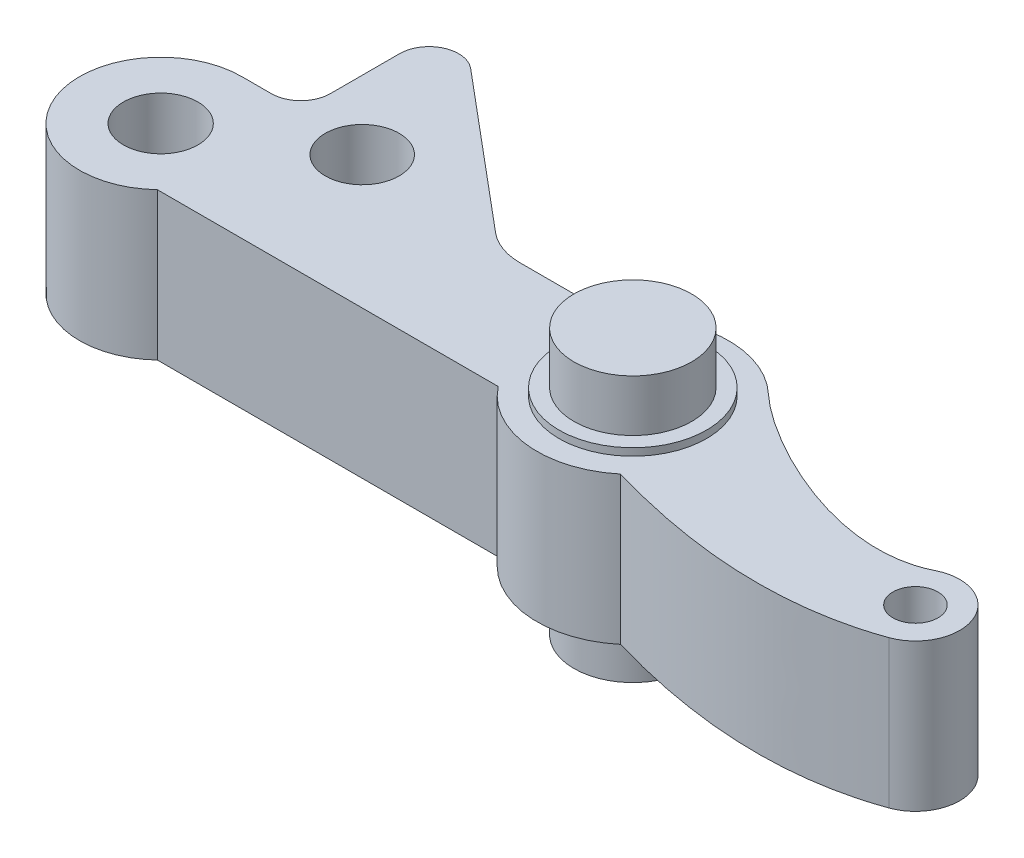
SolidWorks part; units mm, degrees
ref_plane "前视基准面" through (0, 0, 0) normal (0, 0, 1) x (1, 0, 0)
ref_plane "上视基准面" through (0, 0, 0) normal (0, 1, 0) x (1, 0, 0)
ref_plane "右视基准面" through (0, 0, 0) normal (1, 0, 0) x (0, 0, -1)
other "Configuration Table"
sketch "草图1" plane through (0, 0, 0) normal (0, 1, 0) x (1, 0, 0)
  line L0 (-5.1235, -4) -> (-28.2251, -4)
  line L1 (0, 0) -> (-38.4813, 0) construction
  line L2 (-5.1235, 4) -> (-13.1235, 4)
  line L3 (-23.3397, 5) -> (-32, 0) construction
  line L4 (-13.1235, 4) -> (-28, 16.4829)
  line L5 (-28, 16.4829) -> (-28, 5.5)
  line L6 (-32, 5.5) -> (-28, 5.5)
  arc A0 (-5.1235, -4) -> (-5.1235, 4) centre (0, 0) ccw
  arc A1 (-32, 5.5) -> (-28.2251, -4) centre (-32, 0) ccw
  circle A2 centre (-32, 0) radius 2.525
  circle A3 centre (-23.3397, 5) radius 2.505
  dimension "D1" = 13
  dimension "D2" = 11
  dimension "D5" = 5.05
  dimension "D8" = 5.01
  dimension "D3" = 32
  dimension "D4" = 4
  dimension "D6" = 30
  dimension "D7" = 10
  dimension "D9" = 4
  dimension "D10" = 8
  dimension "D11" = 40
extrude "凸台-拉伸1" add sketch "草图1" along normal blind 10
ref_plane "基准面3" through (0, 5, 0) normal (0, -1, 0) x (-1, 0, 0)
sketch "草图2" plane through (0, 5, 0) normal (0, 1, 0) x (1, 0, 0)
  line L0 (0, 0) -> (30.1993, 0) construction
  line L1 (0, 0) -> (21.836, -2.6811) construction
  line L7 (4.1594, -4.9949) -> (15.251, -8.2326) construction
  line L8 (15.251, -8.2326) -> (22.8497, -5.5047) construction
  line L9 (4.4667, 4.7222) -> (7.2849, 2.0565) construction
  line L10 (15.7167, -2.3962) -> (20.4901, 0) construction
  line L11 (7.2849, 2.0565) -> (15.7167, -2.3962) construction
  arc A0 (-5.1235, -4) -> (-5.1235, 4) centre (0, 0) ccw construction
  circle A2 centre (21.836, -2.6811) radius 1.525
  arc A3 (22.8497, -5.5047) -> (20.4901, 0) centre (21.836, -2.6811) ccw
  arc A4 (4.1594, -4.9949) -> (4.4667, 4.7222) centre (0, 0) ccw
  spline S0 degree 2 poles (4.1594, -4.9949) (15.251, -8.2326) (22.8497, -5.5047) knots 0 0 0 1 1 1
  spline S1 degree 3 poles (4.4667, 4.7222) (7.2849, 2.0565) (15.7167, -2.3962) (20.4901, 0) knots 0 0 0 0 1 1 1 1
  dimension "D4" = 3.05
  dimension "D3" = 6
  dimension "D1" = 7
  dimension "D2" = 22
extrude "凸台-拉伸2" add sketch "草图2" along normal mid plane 10 contours A4 S1 A3 S0 A2
sketch "草图3" plane through (0, 10, 0) normal (0, 1, 0) x (1, 0, 0)
  circle A0 centre (0, 0) radius 22
ref_plane "基准面1" through (0, 5, 0) normal (0, 1, 0) x (1, 0, 0)
sketch "草图5" plane through (0, 5, 0) normal (0, 1, 0) x (1, 0, 0)
  circle A0 centre (0, 0) radius 3.99
  dimension "D1" = 7.98
extrude "凸台-拉伸4" add sketch "草图5" along normal mid plane 18
fillet "圆角1" radius 4 1 edges at (-13.1235, 5, -4)
fillet "圆角2" radius 2 1 edges at (-28, 5, -16.4829)
fillet "圆角3" radius 2 1 edges at (-28, 5, -5.5)
sketch "草图6" plane through (0, 10, 0) normal (0, 1, 0) x (1, 0, 0)
  circle A0 centre (0, 0) radius 5
  dimension "D1" = 10
extrude "凸台-拉伸5" add sketch "草图6" along normal blind 0.5
ref_plane "基准面4" through (0, 5, 0) normal (0, 1, 0) x (1, 0, 0)
mirror "镜向1" about plane through (0, 5, 0) normal (0, 1, 0) of "凸台-拉伸5"
